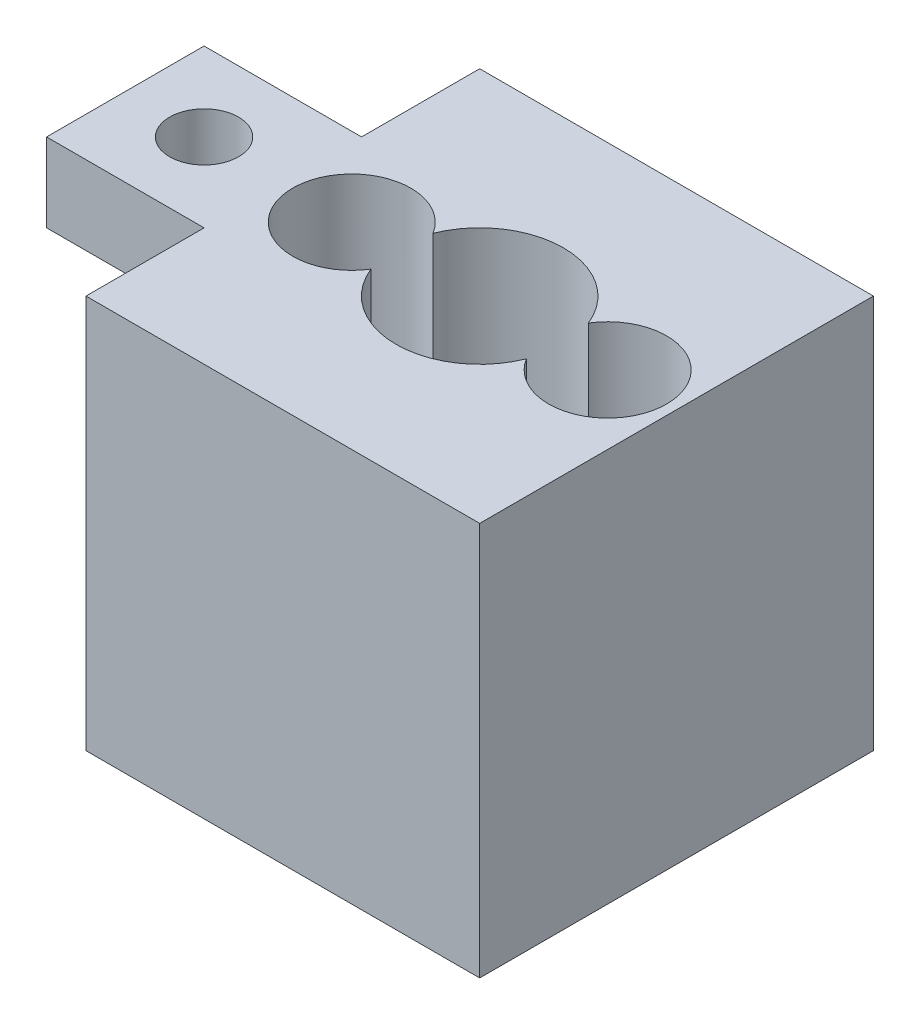
SolidWorks part; units mm, degrees
material "ABS"
ref_plane "Front Plane" through (0, 0, 0) normal (0, 0, 1) x (1, 0, 0)
ref_plane "Top Plane" through (0, 0, 0) normal (0, 1, 0) x (1, 0, 0)
ref_plane "Right Plane" through (0, 0, 0) normal (1, 0, 0) x (0, 0, -1)
sketch "Sketch1" plane through (0, 0, 0) normal (0, 1, 0) x (1, 0, 0)
  line L1 (-10, -10) -> (10, -10)
  line L2 (-10, -10) -> (-10, 10)
  line L3 (-10, 10) -> (10, 10)
  line L4 (10, -10) -> (10, 10)
  line L5 (-10, -10) -> (10, 10) construction
  line L6 (-10, 10) -> (10, -10) construction
  point P0 (0, 0)
  dimension "D1" = 20
  dimension "D2" = 20
extrude "Boss-Extrude1" add sketch "Sketch1" along normal blind 20
sketch "Sketch2" plane through (0, 20, 0) normal (0, 1, 0) x (1, 0, 0)
  circle A0 centre (0, 0) radius 4.25
  dimension "D1" = 8.5
extrude "Cut-Extrude1" cut sketch "Sketch2" against normal blind 10
sketch "Sketch3" plane through (0, 20, 0) normal (0, 1, 0) x (1, 0, 0)
  line L0 (-10, 10) -> (-10, -10) construction
  line L1 (10, -10) -> (10, 10) construction
  circle A0 centre (-6.5, 0) radius 1.75
  circle A1 centre (6.5, 0) radius 1.75
  dimension "D1" = 3.5
  dimension "D2" = 3.5
  dimension "D3" = 3.5
  dimension "D4" = 3.5
extrude "Cut-Extrude2" cut sketch "Sketch3" against normal through all
sketch "Sketch4" plane through (0, 20, 0) normal (0, 1, 0) x (1, 0, 0)
  circle A0 centre (-6.5, 0) radius 3
  circle A1 centre (6.5, 0) radius 3
  dimension "D1" = 6
  dimension "D2" = 6
extrude "Cut-Extrude3" cut sketch "Sketch4" against normal blind 15
sketch "Sketch5" plane through (-10, 0, 0) normal (-1, 0, 0) x (0, 0, 1)
  line L0 (-10, 20) -> (10, 20) construction
  line L1 (4, 20) -> (-4, 20)
  line L2 (4, 20) -> (4, 16)
  line L3 (4, 16) -> (-4, 16)
  line L4 (-4, 20) -> (-4, 16)
  line L5 (4, 20) -> (-4, 16) construction
  line L6 (4, 16) -> (-4, 20) construction
  line L9 (-10, 20) -> (-10, 0) construction
  dimension "D1" = 8
  dimension "D2" = 4
  dimension "D3" = 6
extrude "Boss-Extrude2" add sketch "Sketch5" along normal blind 8
sketch "Sketch6" plane through (0, 16, 0) normal (0, -1, 0) x (1, 0, 0)
  line L0 (-18, -4) -> (-18, 4) construction
  line L2 (-18, 4) -> (-10, 4) construction
  circle A0 centre (-14, 0) radius 1.75
  dimension "D1" = 3.5
  dimension "D2" = 4
  dimension "D3" = 4
extrude "Cut-Extrude4" cut sketch "Sketch6" against normal through all and the other way through all
